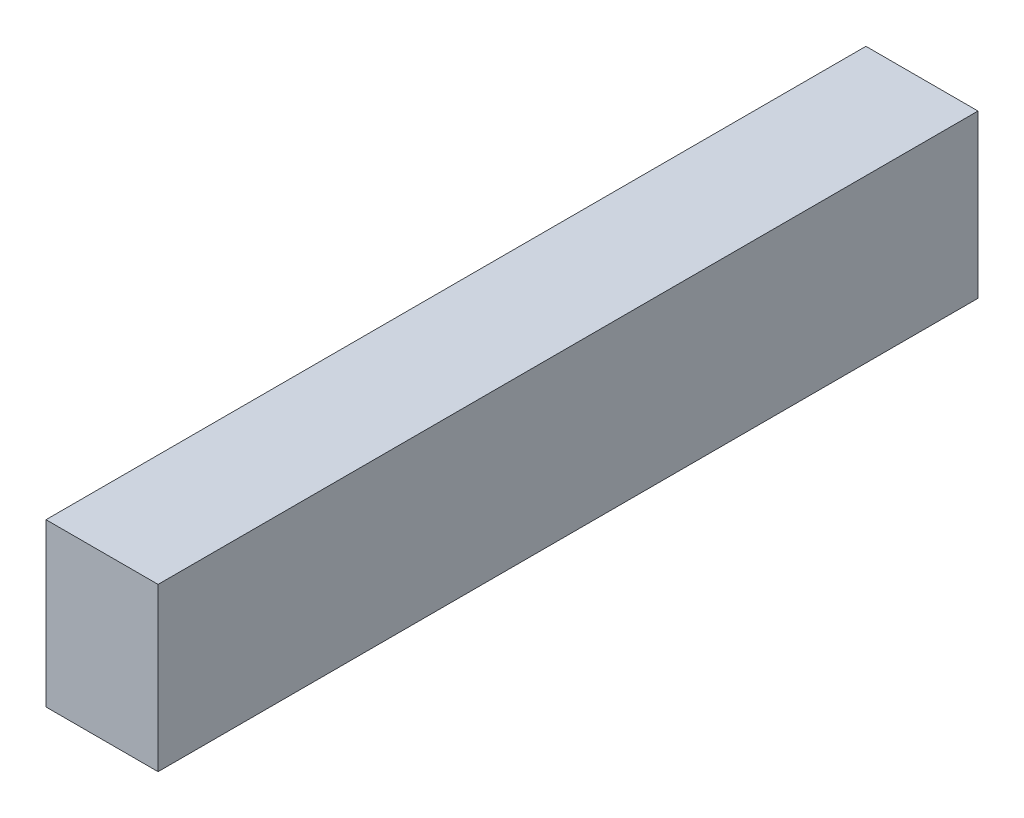
SolidWorks part; units mm, degrees
material "Brass"
ref_plane "Front Plane" through (0, 0, 0) normal (0, 0, 1) x (1, 0, 0)
ref_plane "Top Plane" through (0, 0, 0) normal (0, 1, 0) x (1, 0, 0)
ref_plane "Right Plane" through (0, 0, 0) normal (1, 0, 0) x (0, 0, -1)
sketch "Sketch1" plane through (0, 0, 0) normal (0, 1, 0) x (1, 0, 0)
  line L1 (0, 0) -> (3.8, 0)
  line L2 (0, 0) -> (0, 27.8)
  line L3 (0, 27.8) -> (3.8, 27.8)
  line L4 (3.8, 0) -> (3.8, 27.8)
  dimension "D1" = 3.8
  dimension "D2" = 27.8
extrude "Boss-Extrude1" add sketch "Sketch1" along normal blind 5.5
